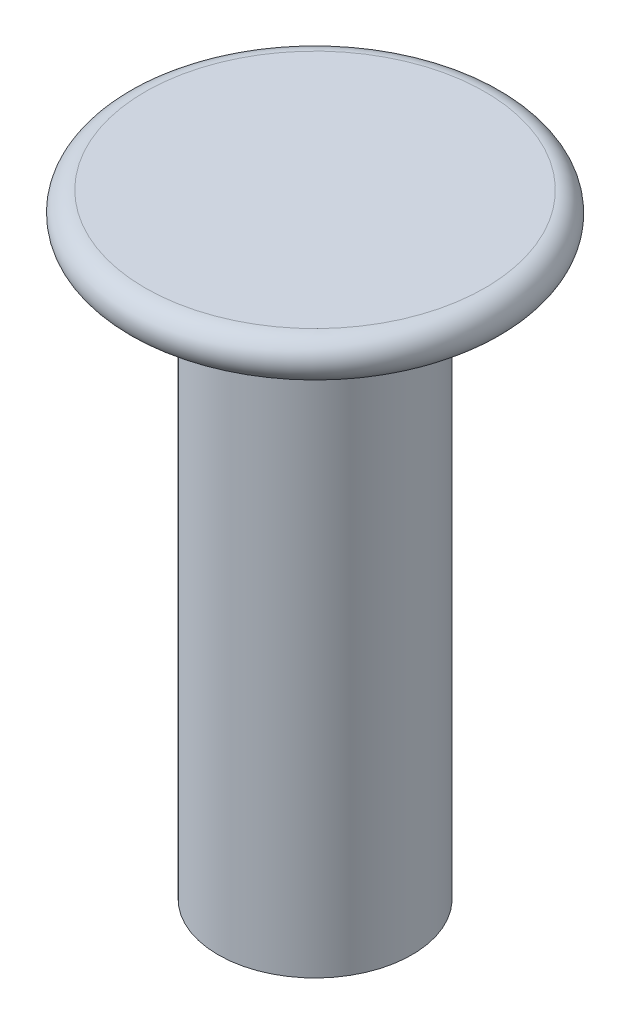
SolidWorks part; units mm, degrees
material "Plain Carbon Steel"
ref_plane "Front Plane" through (0, 0, 0) normal (0, 0, 1) x (1, 0, 0)
ref_plane "Top Plane" through (0, 0, 0) normal (0, 1, 0) x (1, 0, 0)
ref_plane "Right Plane" through (0, 0, 0) normal (1, 0, 0) x (0, 0, -1)
sketch "Sketch2" plane through (0, 0, 0) normal (0, 0, 1) x (1, 0, 0)
  line L0 (0, 94.6089) -> (0, -124.2387) construction
  line L1 (-109.7248, 0) -> (112.8211, 0) construction
  line L4 (1.5875, -1.397) -> (1.5875, -10.0584)
  line L5 (1.5875, -10.0584) -> (0, -10.0584)
  line L6 (0, -10.0584) -> (0, 0)
  line L7 (0, 0) -> (2.7837, 0)
  line L8 (1.5875, -1.397) -> (2.9476, -0.6118)
  line L9 (3.1115, 3.28) -> (3.1115, -4.1331) construction
  line L10 (1.5875, -1.397) -> (12.4953, 4.9006) construction
  arc A0 (2.7837, 0) -> (2.9476, -0.6118) centre (2.7837, -0.3278) cw
  point P12 (4.0072, 0)
  dimension "D1" = 3.1115
  dimension "D2" = 60
  dimension "D3" = 1.5875
  dimension "D4" = 8.6614
  dimension "D5" = 1.397
revolve "Revolve1" add sketch "Sketch2" angle 360 about L0
